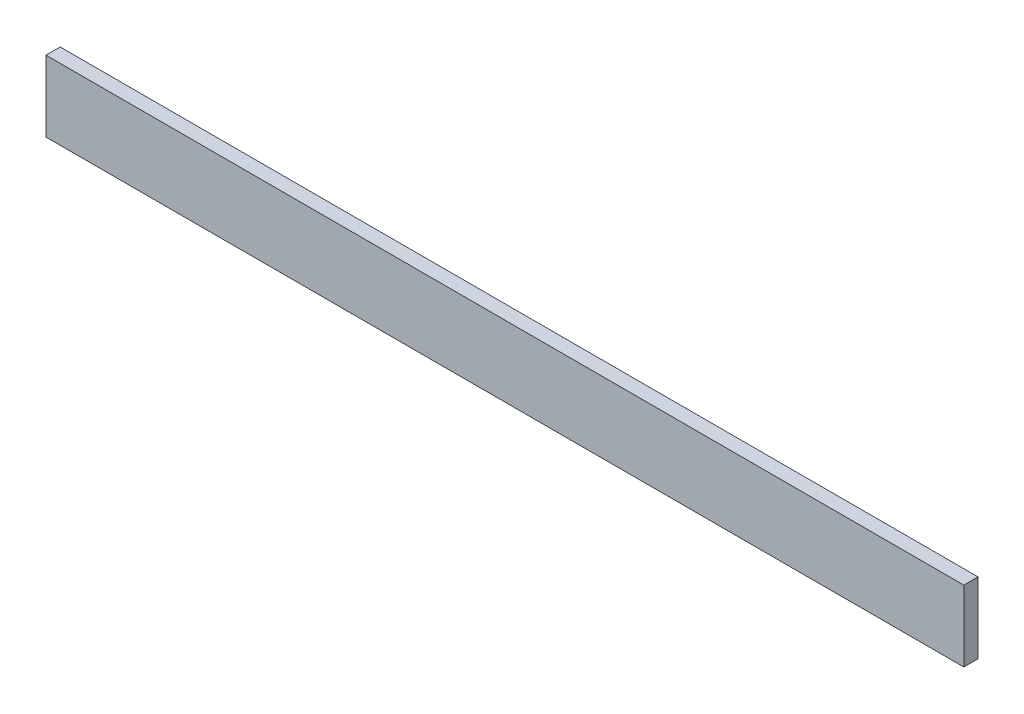
SolidWorks part; units mm, degrees
material "Pine"
ref_plane "Piano frontale" through (0, 0, 0) normal (0, 0, 1) x (1, 0, 0)
ref_plane "Piano superiore" through (0, 0, 0) normal (0, 1, 0) x (1, 0, 0)
ref_plane "Piano destro" through (0, 0, 0) normal (1, 0, 0) x (0, 0, -1)
sketch "Sketch1" plane through (0, 0, 0) normal (0, 0, 1) x (1, 0, 0)
  line L1 (0, 0) -> (97, 0)
  line L2 (0, 0) -> (0, 7.5)
  line L3 (0, 7.5) -> (97, 7.5)
  line L4 (97, 0) -> (97, 7.5)
  dimension "D1" = 97
  dimension "D2" = 7.5
extrude "Boss-Extrude1" add sketch "Sketch1" along normal blind 1.5
scale "Scale1" scale about origin uniform scaling yes scale factor 10
